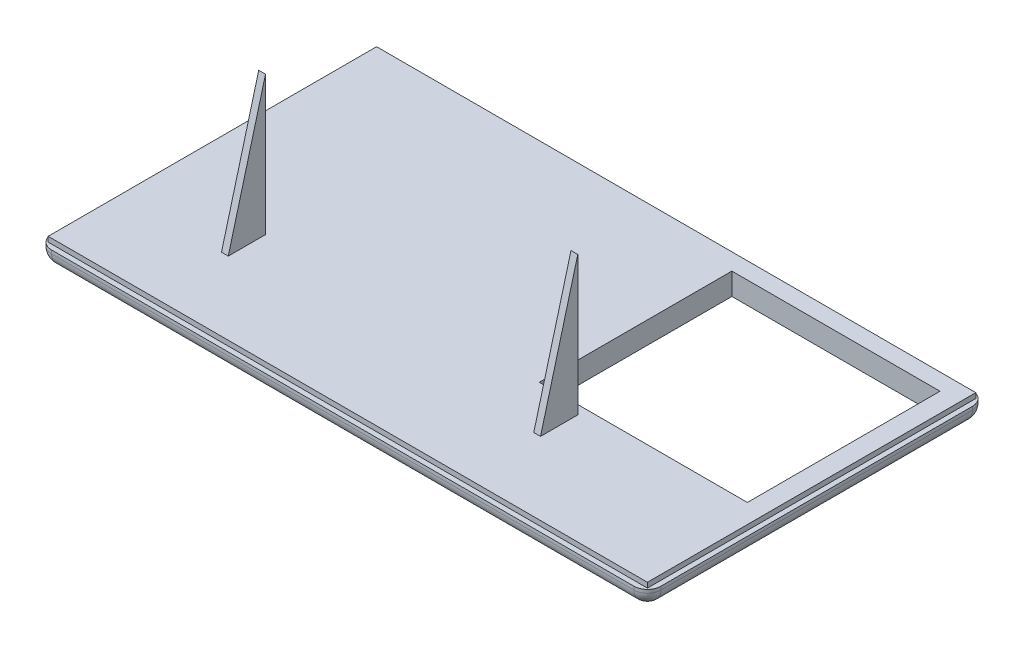
SolidWorks part; units mm, degrees
ref_plane "Front Plane" through (0, 0, 0) normal (0, 0, 1) x (1, 0, 0)
ref_plane "Top Plane" through (0, 0, 0) normal (0, 1, 0) x (1, 0, 0)
ref_plane "Right Plane" through (0, 0, 0) normal (1, 0, 0) x (0, 0, -1)
sketch "Sketch1" plane through (0, 0, 0) normal (0, 1, 0) x (1, 0, 0)
  line L1 (-78.5075, 39.5522) -> (101.4925, 39.5522)
  line L2 (-78.5075, 39.5522) -> (-78.5075, -60.4478)
  line L3 (-78.5075, -60.4478) -> (101.4925, -60.4478)
  line L4 (101.4925, 39.5522) -> (101.4925, -60.4478)
  dimension "D1" = 100
  dimension "D2" = 180
extrude "Boss-Extrude1" add sketch "Sketch1" along normal blind 5
sketch "Sketch2" plane through (0, 5, 0) normal (0, 1, 0) x (1, 0, 0)
  line L0 (-78.5075, 39.5522) -> (-78.5075, -60.4478) construction
  line L1 (-77.0075, 38.0522) -> (99.9925, 38.0522)
  line L2 (-77.0075, 38.0522) -> (-77.0075, -58.9478)
  line L3 (-77.0075, -58.9478) -> (99.9925, -58.9478)
  line L4 (99.9925, 38.0522) -> (99.9925, -58.9478)
  line L5 (101.4925, 39.5522) -> (-78.5075, 39.5522) construction
  point P4 (-77.0075, -10.4478)
  point P7 (-78.5075, -10.4478)
  point P8 (11.4925, 38.0522)
  point P11 (11.4925, 39.5522)
  dimension "D1" = 97
  dimension "D2" = 177
extrude "Boss-Extrude2" add sketch "Sketch2" along normal blind 1.5
sketch "Sketch3" plane through (0, 6.5, 0) normal (0, 1, 0) x (1, 0, 0)
  line L1 (32.8708, 33.1262) -> (94.3388, 33.1262)
  line L2 (32.8708, 33.1262) -> (32.8708, -23.7698)
  line L3 (32.8708, -23.7698) -> (94.3388, -23.7698)
  line L4 (94.3388, 33.1262) -> (94.3388, -23.7698)
  dimension "D1" = 56.896
  dimension "41.468mm" = 61.468
extrude "Cut-Extrude1" cut sketch "Sketch3" against normal up to next contours L2 L1 L4 L3
fillet "Fillet3" radius 4 4 edges at (-78.5075, 2.5, 60.4478) (-78.5075, 2.5, -39.5522) (101.4925, 2.5, -39.5522) (101.4925, 2.5, 60.4478)
fillet "Fillet4" radius 4 8 edges at (100.321, 0, -38.3807) (101.4925, 0, 10.4478) (100.321, 0, 59.2762) (11.4925, 0, 60.4478) (-77.3359, 0, 59.2762) (-78.5075, 0, 10.4478) (-77.3359, 0, -38.3807) (11.4925, 0, -39.5522)
sketch "Sketch5" plane through (0, 6.5, 0) normal (0, 1, 0) x (1, 0, 0)
  line L0 (-77.0075, -58.9478) -> (-77.0075, -37.4278)
  line L1 (-77.0075, 38.0522) -> (-77.0075, -58.9478) construction
  line L4 (-77.0075, -37.4278) -> (-47.3378, -37.4278)
  line L5 (-47.3378, -37.4278) -> (-45.3378, -37.4278)
  line L9 (-47.3378, -37.4278) -> (-47.3378, -26.4278)
  line L10 (-47.3378, -26.4278) -> (-45.3378, -26.4278)
  line L11 (-45.3378, -37.4278) -> (-45.3378, -26.4278)
  dimension "D1" = 2
  dimension "D3" = 11
extrude "Boss-Extrude3" add sketch "Sketch5" along normal blind 55 contours L5 L11 L10 L9
sketch "Sketch7" plane through (0, 6.5, 0) normal (0, 1, 0) x (1, 0, 0)
  line L2 (99.9925, -58.9478) -> (99.9925, 38.0522) construction
  line L3 (99.9925, -37.4278) -> (46.8993, -37.4278)
  line L4 (46.8993, -37.4278) -> (44.8993, -37.4278)
  line L5 (46.8993, -37.4278) -> (46.8993, -26.4278)
  line L6 (46.8993, -26.4278) -> (44.8993, -26.4278)
  line L7 (44.8993, -37.4278) -> (44.8993, -26.4278)
  dimension "D1" = 11
  dimension "D2" = 2
extrude "Boss-Extrude4" add sketch "Sketch7" along normal blind 55 contours L4 L7 L6 L5
sketch "Sketch8" plane through (46.8993, 0, 0) normal (1, 0, 0) x (0, 0, -1)
  line L0 (-37.4278, 6.5) -> (-22.6906, 61.5)
  line L1 (-37.4278, 61.5) -> (-26.4278, 61.5) construction
extrude "Cut-Extrude3" cut sketch "Sketch8" against normal through all and the other way through all
